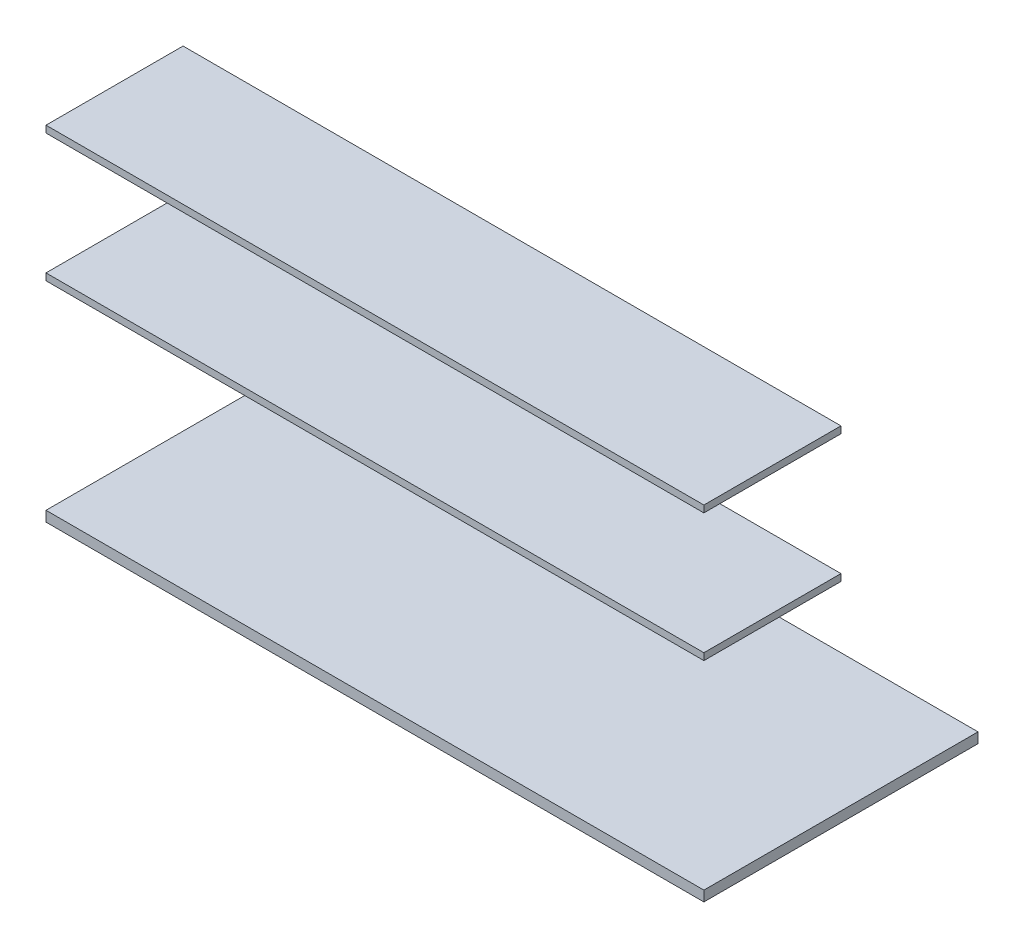
SolidWorks part; units mm, degrees
material "Maple"
ref_plane "Front Plane" through (0, 0, 0) normal (0, 0, 1) x (1, 0, 0)
ref_plane "Top Plane" through (0, 0, 0) normal (0, 1, 0) x (1, 0, 0)
ref_plane "Right Plane" through (0, 0, 0) normal (1, 0, 0) x (0, 0, -1)
sketch "Sketch1" plane through (0, 0, 0) normal (1, 0, 0) x (0, 0, -1)
  line L0 (0, 0) -> (762, 0)
  line L1 (762, 0) -> (762, 28.575)
  line L2 (762, 28.575) -> (0, 28.575)
  line L3 (0, 28.575) -> (0, 0)
  line L4 (0, 581.025) -> (0, 600.075)
  line L5 (0, 600.075) -> (381, 600.075)
  line L6 (381, 600.075) -> (381, 581.025)
  line L7 (381, 581.025) -> (0, 581.025)
  line L9 (0, 936.625) -> (381, 936.625)
  line L10 (0, 936.625) -> (0, 955.675)
  line L11 (0, 955.675) -> (381, 955.675)
  line L12 (381, 936.625) -> (381, 955.675)
  dimension "D1" = 762
  dimension "D2" = 28.575
  dimension "D3" = 19.05
  dimension "D4" = 381
  dimension "D5" = 552.45
  dimension "D6" = 19.05
  dimension "D7" = 381
  dimension "D8" = 336.55
extrude "Boss-Extrude1" add sketch "Sketch1" against normal blind 1828.8
